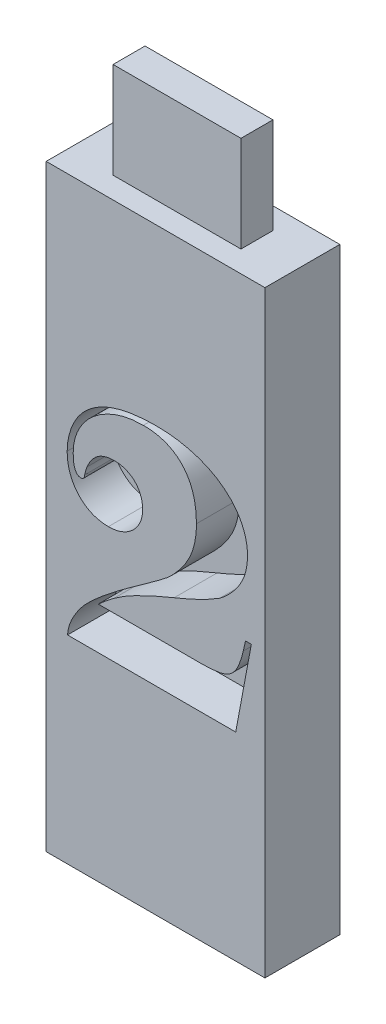
SolidWorks part; units mm, degrees
ref_plane "Front Plane" through (0, 0, 0) normal (0, 0, 1) x (1, 0, 0)
ref_plane "Top Plane" through (0, 0, 0) normal (0, 1, 0) x (1, 0, 0)
ref_plane "Right Plane" through (0, 0, 0) normal (1, 0, 0) x (0, 0, -1)
sketch "Sketch1" plane through (0, 0, 0) normal (0, 0, 1) x (1, 0, 0)
  line L1 (-8.69, -23.749) -> (8.69, -23.749)
  line L2 (-8.69, -23.749) -> (-8.69, 23.749)
  line L3 (-8.69, 23.749) -> (8.69, 23.749)
  line L4 (8.69, -23.749) -> (8.69, 23.749)
  line L5 (-8.69, -23.749) -> (8.69, 23.749) construction
  line L6 (-8.69, 23.749) -> (8.69, -23.749) construction
  point P0 (0, 0)
  dimension "D1" = 17.38
  dimension "D2" = 47.498
extrude "Boss-Extrude1" add sketch "Sketch1" along normal blind 5.95
sketch "Sketch2" plane through (0, 0, 5.95) normal (0, 0, 1) x (1, 0, 0)
  line L0 (0, 23.749) -> (0, -23.749) construction
  line L1 (8.69, 23.749) -> (-8.69, 23.749) construction
  line L2 (-8.69, -23.749) -> (8.69, -23.749) construction
  line L3 (0, -23.749) -> (0, 0) construction
  line L4 (0, 0) -> (-8.69, 0) construction
  line L5 (-8.69, 23.749) -> (-8.69, -23.749) construction
  line L6 (-8.69, 0) -> (8.69, 0) construction
  line L7 (8.69, -23.749) -> (8.69, 23.749) construction
  line L8 (-8.69, -23.749) -> (8.69, -23.749) construction
  line L9 (-8.69, -21.209) -> (8.69, -21.209) construction
  line L10 (-8.69, -18.669) -> (8.69, -18.669) construction
  line L11 (-8.69, -16.129) -> (8.69, -16.129) construction
  line L12 (-8.69, -13.589) -> (8.69, -13.589) construction
  line L13 (-8.69, -11.049) -> (8.69, -11.049) construction
  line L14 (-8.69, -8.509) -> (8.69, -8.509) construction
  line L15 (-8.69, -5.969) -> (8.69, -5.969) construction
  line L16 (-8.69, -3.429) -> (8.69, -3.429) construction
  line L17 (-8.69, -0.889) -> (8.69, -0.889) construction
  line L18 (-8.69, 1.651) -> (8.69, 1.651) construction
  line L19 (-8.69, 4.191) -> (8.69, 4.191) construction
  line L20 (-8.69, 6.731) -> (8.69, 6.731) construction
  line L21 (-8.69, 9.271) -> (8.69, 9.271) construction
  line L22 (-8.69, 11.811) -> (8.69, 11.811) construction
  line L23 (-8.69, 14.351) -> (8.69, 14.351) construction
  line L24 (-8.69, 16.891) -> (8.69, 16.891) construction
  line L25 (-8.69, 19.431) -> (8.69, 19.431) construction
  line L26 (-8.69, 21.971) -> (8.69, 21.971) construction
  line L27 (-8.69, 23.749) -> (-8.69, -23.749) construction
  line L28 (-6.15, 23.749) -> (-6.15, -23.749) construction
  line L29 (-3.61, 23.749) -> (-3.61, -23.749) construction
  line L30 (-1.07, 23.749) -> (-1.07, -23.749) construction
  line L31 (1.47, 23.749) -> (1.47, -23.749) construction
  line L32 (4.01, 23.749) -> (4.01, -23.749) construction
  line L33 (6.55, 23.749) -> (6.55, -23.749) construction
  text T0 "2\r\n\r\n" font "Engravers MT" height in points 72
  dimension "D1" = 19
  dimension "D2" = 2.54
  dimension "D4" = 2.54
  dimension "D3" = 7
extrude "Cut-Extrude1" cut sketch "Sketch2" against normal blind 3.41
sketch "Sketch3" plane through (0, 23.749, 0) normal (0, 1, 0) x (1, 0, 0)
  line L0 (0, 0) -> (0, -5.95) construction
  line L1 (8.69, -5.95) -> (-8.69, -5.95) construction
  line L2 (0, -5.95) -> (0, -2.975) construction
  line L3 (0, -2.975) -> (-8.69, -2.975) construction
  line L4 (-8.69, -5.95) -> (-8.69, 0) construction
  line L5 (-8.69, -2.975) -> (8.69, -2.975) construction
  line L6 (8.69, -5.95) -> (8.69, 0) construction
  line L8 (-5.08, -4.245) -> (5.08, -4.245)
  line L9 (-5.08, -4.245) -> (-5.08, -1.705)
  line L10 (-5.08, -1.705) -> (5.08, -1.705)
  line L11 (5.08, -4.245) -> (5.08, -1.705)
  line L12 (-5.08, -4.245) -> (5.08, -1.705) construction
  line L13 (-5.08, -1.705) -> (5.08, -4.245) construction
  dimension "D1" = 2.54
  dimension "D2" = 10.16
extrude "Boss-Extrude2" add sketch "Sketch3" along normal blind 7.62
